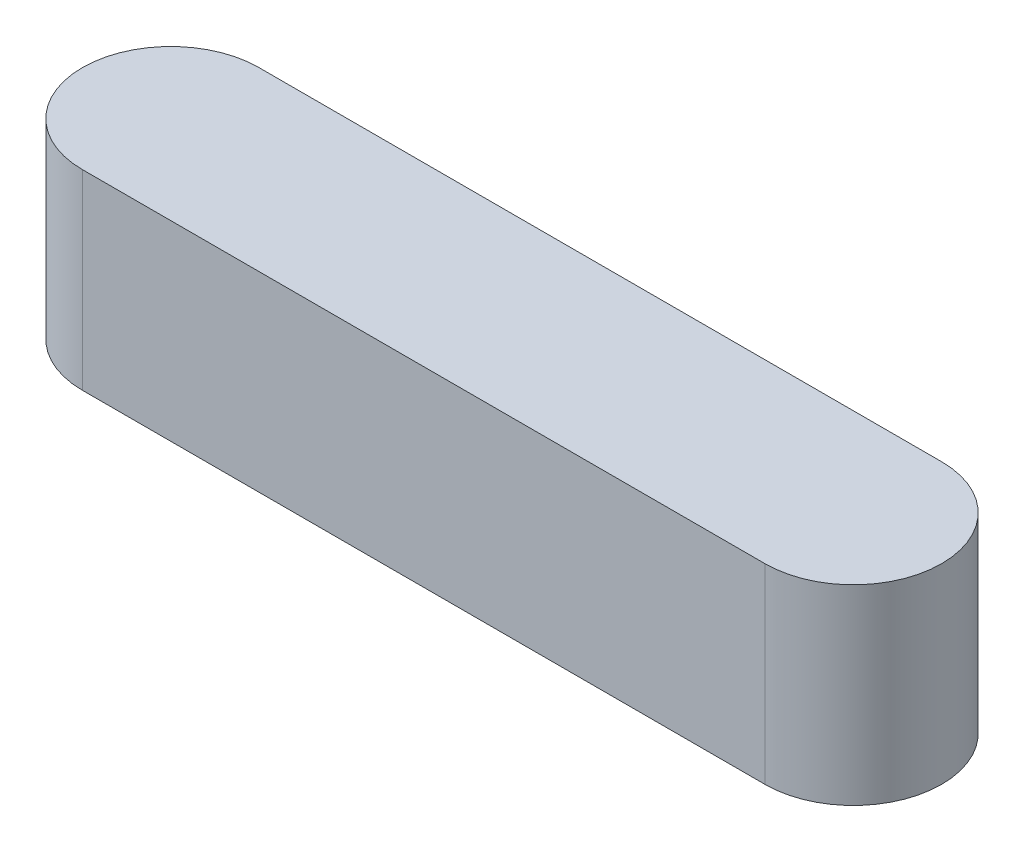
SolidWorks part; units mm, degrees
ref_plane "Front Plane" through (0, 0, 0) normal (0, 0, 1) x (1, 0, 0)
ref_plane "Top Plane" through (0, 0, 0) normal (0, 1, 0) x (1, 0, 0)
ref_plane "Right Plane" through (0, 0, 0) normal (1, 0, 0) x (0, 0, -1)
sketch "Sketch1" plane through (0, 0, 0) normal (0, 1, 0) x (1, 0, 0)
  line L0 (-17.2531, 0.05) -> (7.7469, 0.05) construction
  line L1 (26.5978, 0.05) -> (-26.5978, 0.05) construction
  line L2 (-17.2531, 3.2841) -> (7.7469, 3.2841)
  line L3 (-17.2531, -3.1841) -> (7.7469, -3.1841)
  arc A0 (-17.2531, 3.2841) -> (-17.2531, -3.1841) centre (-17.2531, 0.05) ccw
  arc A1 (7.7469, -3.1841) -> (7.7469, 3.2841) centre (7.7469, 0.05) ccw
  point P2 (-4.7531, 0.05)
  dimension "D2" = 3.2341
  dimension "D1" = 25
  dimension "D3" = 6.4682
extrude "Boss-Extrude1" add sketch "Sketch1" along normal blind 2 and the other way blind 5
